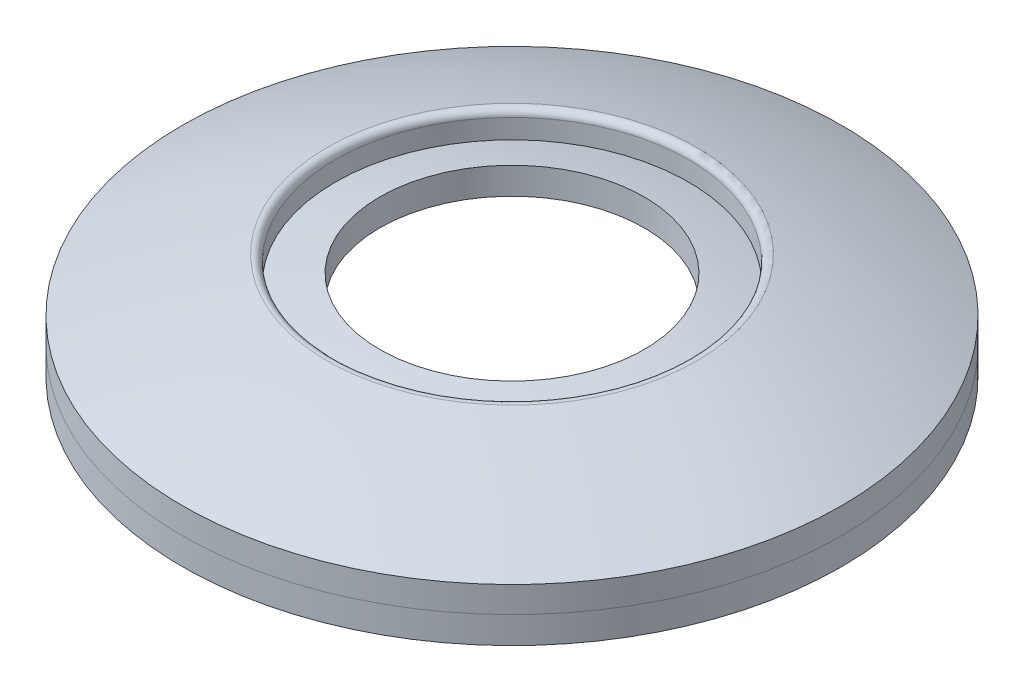
SolidWorks part; units mm, degrees
ref_plane "Front" through (0, 0, 0) normal (0, 0, 1) x (1, 0, 0)
ref_plane "Top" through (0, 0, 0) normal (0, 1, 0) x (1, 0, 0)
ref_plane "Right" through (0, 0, 0) normal (1, 0, 0) x (0, 0, -1)
sketch "Sketch1" plane through (0, 0, 0) normal (1, 0, 0) x (0, 0, -1)
  line L0 (0, -1.6573) -> (0, 1.6573) construction
  line L1 (0, 0) -> (-10.287, 0) construction
  line L2 (0, 0) -> (10.287, 0) construction
  line L3 (0, 1.6573) -> (5.5118, 1.6573) construction
  line L4 (10.287, 0) -> (10.287, -1.6573) construction
  point P4 (0, 0)
  point P6 (0, 1.6573)
  point P7 (0, -1.6573)
  dimension "OD (A)" = 20.574
  dimension "D1" = 11.0236
  dimension "Thickness Range" = 3.3147
sketch "Sketch2" plane through (0, 0, 0) normal (0, 0, 1) x (1, 0, 0)
  line L0 (0, -1.6573) -> (0, 1.6573) construction
  line L1 (-10.287, -0.8192) -> (10.287, -0.8192) construction
  line L2 (5.5118, -0.8192) -> (-5.5118, -0.8192) construction
  line L4 (-5.5118, 1.6573) -> (-5.5118, -1.6573) construction
  line L5 (-5.5118, 1.6573) -> (-10.287, 1.6573) construction
  line L6 (4.1275, -1.6573) -> (-4.1275, -1.6574) construction
  line L7 (-10.287, -0.8192) -> (-10.287, -0.0064) construction
  line L8 (-10.287, -0.0064) -> (-10.287, 1.6573) construction
  line L9 (-10.287, -0.8192) -> (-10.287, -1.6574) construction
  point P11 (0, 0)
  point P12 (-4.1275, -1.6574)
  point P13 (4.1275, -1.6573)
  point P14 (0, -0.8192)
  point P17 (0, -1.6573)
  point P19 (0, -0.8192)
  point P20 (-5.5118, -0.8192)
  point P21 (5.5118, -0.8192)
  dimension "OD (A)" = 20.574
  dimension "ID (B)" = 11.0236
  dimension "Rubber ID (G)" = 8.255
  dimension "Dome Thickness (D)" = 0.8128
  dimension "Dome Height (E)" = 1.6637
  dimension "Thickness (C)" = 1.651
sketch "Sketch3" plane through (0, 0, 0) normal (0, 0, 1) x (1, 0, 0)
  line L0 (-10.287, -0.0064) -> (-10.287, -0.8192) construction
  line L1 (10.287, -0.0064) -> (10.287, -0.8192) construction
  line L2 (-10.287, -0.8192) -> (-10.1547, -0.8192) construction
  line L3 (-10.287, -0.8192) -> (10.287, -0.8192) construction
  line L4 (-5.5118, 1.6573) -> (-5.5118, 0.8445) construction
  line L5 (-5.5118, 1.6573) -> (-5.5118, -1.6573) construction
  line L6 (10.1547, -0.8192) -> (10.287, -0.8192) construction
  arc A1 (-10.287, -0.0064) -> (10.287, -0.0064) centre (0, -21.8476) cw construction
  arc A3 (-10.1547, -0.8192) -> (10.1547, -0.8192) centre (0, -21.8476) cw construction
sketch "Sketch6" plane through (0, 0, 0) normal (0, 0, 1) x (1, 0, 0)
  line L0 (-10.287, -0.0064) -> (-10.287, -0.8192)
  line L1 (-5.5118, 1.6573) -> (-5.5118, 0.8445) construction
  line L2 (-5.5118, 1.6573) -> (-5.5118, -1.6573) construction
  line L3 (-10.287, -0.8192) -> (-10.1547, -0.8192)
  line L4 (-5.5118, 1.6573) -> (-10.287, 1.6573) construction
  line L5 (-5.5118, 1.4516) -> (-5.5118, 0.8445)
  arc A0 (10.1547, -0.8192) -> (-10.1547, -0.8192) centre (0, -21.8476) ccw construction
  arc A1 (-10.287, -0.0064) -> (-5.771, 1.6503) centre (1.2979, -24.6033) cw
  arc A2 (-5.5118, 0.8445) -> (-10.1547, -0.8192) centre (0, -21.8476) ccw
  arc A4 (-5.771, 1.6503) -> (-5.5118, 1.4516) centre (-5.7175, 1.4516) cw
  arc A5 (10.287, -0.0064) -> (-10.287, -0.0064) centre (0, -21.8476) ccw construction
  dimension "D1" = 0.2057
revolve "Revolve3" add sketch "Sketch6" angle 360 about L0
sketch "Sketch7" plane through (0, 0, 0) normal (0, 0, 1) x (1, 0, 0)
  line L0 (-10.287, -0.8192) -> (-10.287, -1.6574)
  line L1 (0, -1.6573) -> (0, 1.6573) construction
  line L2 (0, 0.8192) -> (0, 1.6573) construction
  line L3 (-4.1275, 1.1367) -> (-4.1275, 0.2985)
  line L4 (-4.1275, -1.6574) -> (-4.1275, 1.1367) construction
  line L5 (-10.287, -0.8192) -> (-10.1547, -0.8192)
  line L6 (-10.287, -1.6574) -> (-9.992, -1.6574)
  line L7 (9.992, -1.6574) -> (10.287, -1.6574) construction
  line L11 (10.287, -1.6574) -> (10.287, -0.8192) construction
  arc A1 (-9.992, -1.6574) -> (9.992, -1.6574) centre (0, -21.8476) cw construction
  arc A2 (10.1547, -0.8192) -> (-10.1547, -0.8192) centre (0, -21.8476) ccw construction
  arc A3 (-10.1547, -0.8192) -> (-4.1275, 1.1367) centre (0, -21.8476) cw
  arc A4 (10.1547, -0.8192) -> (-10.1547, -0.8192) centre (0, -21.8476) ccw construction
  arc A5 (-9.992, -1.6574) -> (-4.1275, 0.2985) centre (0, -21.8476) cw
revolve "Revolve4" add sketch "Sketch7" angle 360 about L0
equation "\"OD (A)@Sketch2\"=\"OD (A)@Sketch1\""
equation "\"D1@Sketch1\"=\"id (b)@Sketch2\""
equation "\"D1@Sketch6\"=\"OD (A)@Sketch1\"*.01"
